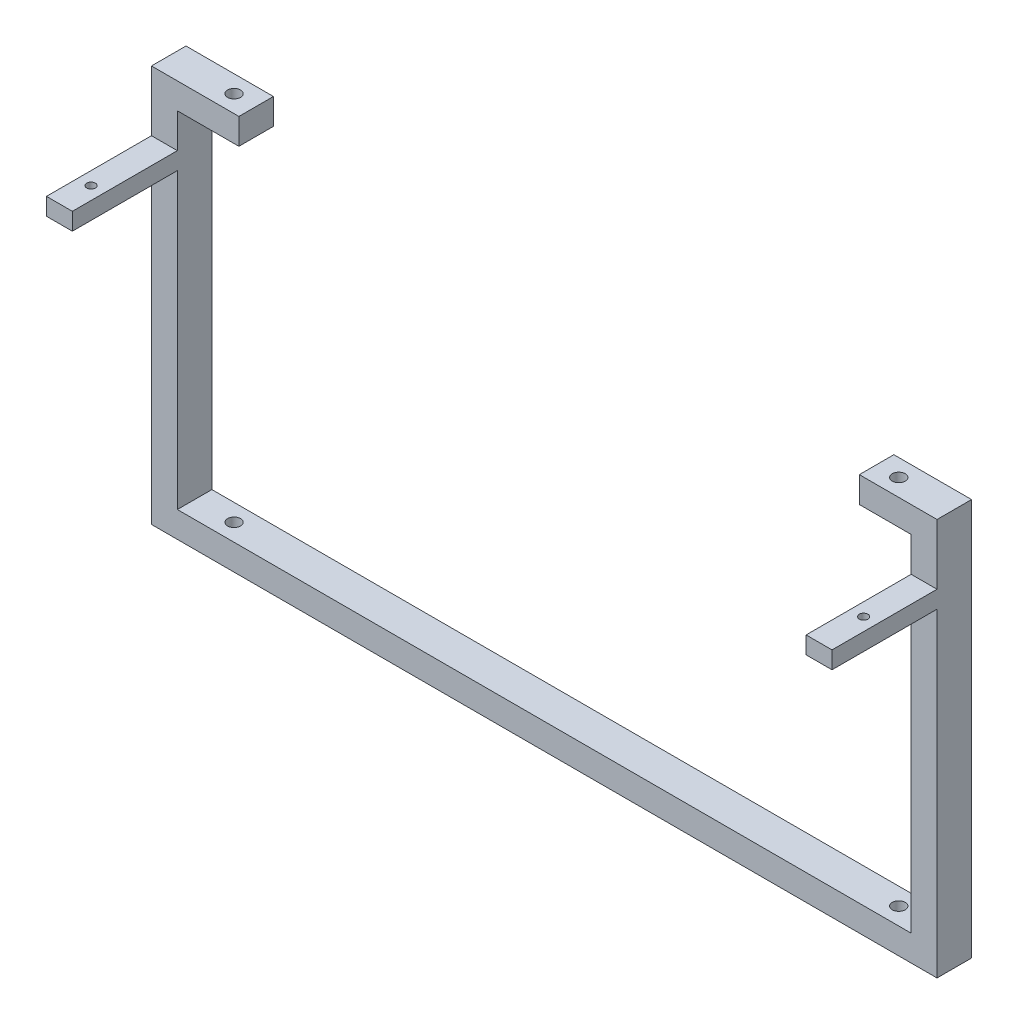
SolidWorks part; units mm, degrees
ref_plane "Plan de face" through (0, 0, 0) normal (0, 0, 1) x (1, 0, 0)
ref_plane "Plan de dessus" through (0, 0, 0) normal (0, 1, 0) x (1, 0, 0)
ref_plane "Plan de droite" through (0, 0, 0) normal (1, 0, 0) x (0, 0, -1)
sketch "Esquisse1" plane through (0, 0, 0) normal (0, 0, 1) x (1, 0, 0)
  line L0 (6.8625, 0) -> (-135.7181, 0)
  line L1 (-135.7181, -800) -> (1564.2819, -800)
  line L2 (-135.7181, 0) -> (-135.7181, -800)
  line L3 (6.8625, 60) -> (-195.7181, 60)
  line L4 (-195.7181, 60) -> (-195.7181, -860)
  line L5 (-195.7181, -860) -> (1624.2819, -860)
  line L6 (6.8625, 60) -> (6.8625, 0)
  line L7 (-135.7181, -800) -> (0, -800) construction
  line L8 (-195.7181, -860) -> (0, -860) construction
  line L9 (1624.2819, -860) -> (1624.2819, 60)
  line L10 (1624.2819, 60) -> (1444.2768, 60)
  line L11 (1444.2768, 60) -> (1444.2768, 0)
  line L12 (1444.2768, 0) -> (1564.2819, 0)
  line L13 (1564.2819, 0) -> (1564.2819, -800)
  dimension "D2" = 800
  dimension "D3" = 60
  dimension "D4" = 60
  dimension "D5" = 1700
  dimension "D1" = 60
extrude "Boss.-Extru.1" add sketch "Esquisse1" along normal blind 80
sketch "Esquisse2" plane through (0, 60, 0) normal (0, 1, 0) x (1, 0, 0)
  circle A0 centre (-44.3949, -40) radius 15
  circle A1 centre (1495.6051, -40) radius 15
  dimension "D1" = 30
  dimension "D2" = 30
  dimension "D3" = 1540
extrude "Enlèv. mat.-Extru.1" cut sketch "Esquisse2" against normal through all
ref_plane "Plan1" through (0, -100, 0) normal (0, 1, 0) x (1, 0, 0)
sketch "Esquisse3" plane through (0, -100, 0) normal (0, 1, 0) x (1, 0, 0)
  line L0 (-195.7181, -80) -> (-195.7181, 0) construction
  line L1 (-195.7181, -40) -> (-135.7181, -40)
  line L2 (-195.7181, -40) -> (-195.7181, -323.2908)
  line L3 (-195.7181, -323.2908) -> (-135.7181, -323.2908)
  line L4 (-135.7181, -40) -> (-135.7181, -323.2908)
  line L5 (1624.2819, -80) -> (1624.2819, 0) construction
  line L7 (1624.2819, -40) -> (1564.2819, -40)
  line L8 (1624.2819, -40) -> (1624.2819, -323.2908)
  line L9 (1624.2819, -323.2908) -> (1564.2819, -323.2908)
  line L10 (1564.2819, -40) -> (1564.2819, -323.2908)
  circle A0 centre (-165.7181, -250) radius 10
  circle A1 centre (1594.2819, -220) radius 10
  circle A2 centre (-44.3949, -40) radius 15 construction
  circle A3 centre (1495.6051, -40) radius 15 construction
  dimension "D3" = 20
  dimension "D4" = 20
  dimension "D5" = 30
  dimension "D6" = 210
  dimension "D7" = 30
  dimension "D8" = 180
  dimension "D1" = 60
  dimension "D2" = 60
extrude "Boss.-Extru.2" add sketch "Esquisse3" along normal mid plane 40
